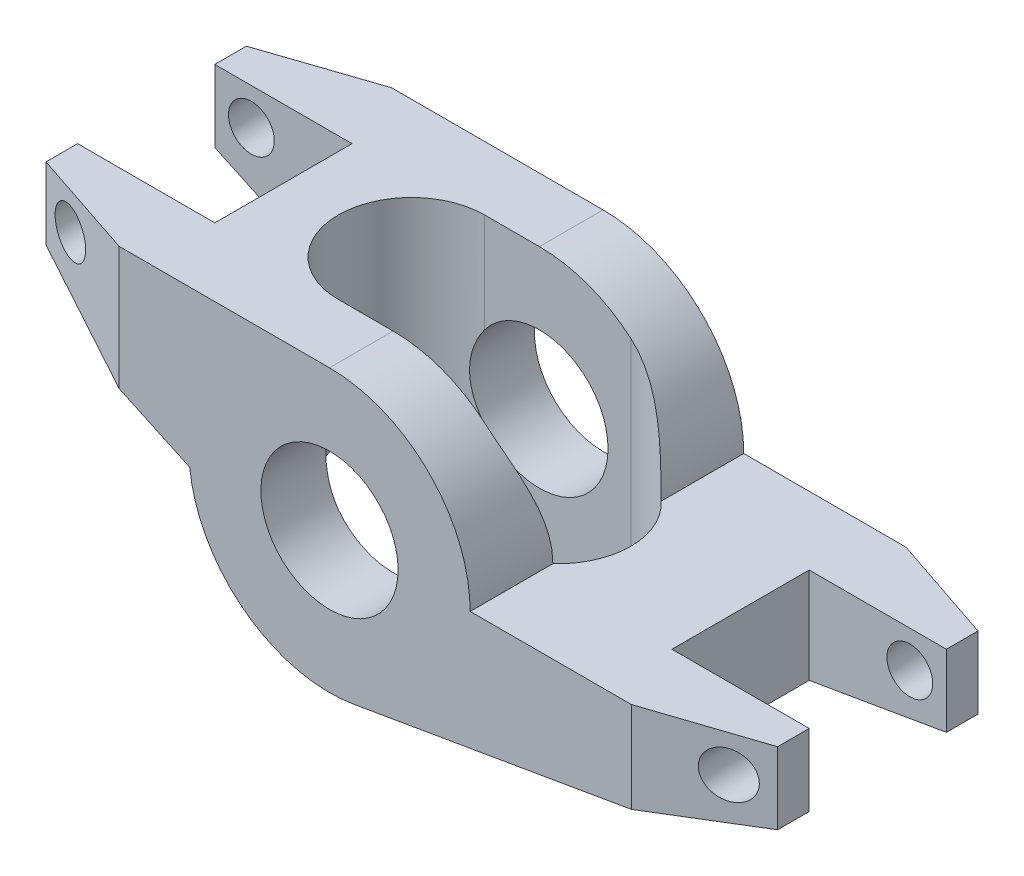
SolidWorks part; units mm, degrees
ref_plane "Front Plane" through (0, 0, 0) normal (0, 0, 1) x (1, 0, 0)
ref_plane "Top Plane" through (0, 0, 0) normal (0, 1, 0) x (1, 0, 0)
ref_plane "Right Plane" through (0, 0, 0) normal (1, 0, 0) x (0, 0, -1)
sketch "Sketch1" plane through (0, 0, 0) normal (0, 0, 1) x (1, 0, 0)
  line L0 (0, 9.77) -> (-22.23, 9.77)
  line L1 (-22.23, 9.77) -> (-22.23, 4.77)
  line L2 (-22.23, 4.77) -> (-9.7115, -1.0675)
  line L3 (9.77, 0) -> (28.58, 0)
  line L4 (28.58, 0) -> (28.58, -5)
  line L5 (28.58, -5) -> (1.6553, -9.6287)
  arc A0 (9.77, 0) -> (0, 9.77) centre (0, 0) ccw
  circle A1 centre (0, 0) radius 4.765
  arc A2 (-9.7115, -1.0675) -> (1.6553, -9.6287) centre (0, 0) ccw
  dimension "D1" = 19.54
  dimension "D2" = 9.53
  dimension "D3" = 22.23
  dimension "D4" = 5
  dimension "D5" = 25
  dimension "D6" = 28.58
extrude "Boss-Extrude1" add sketch "Sketch1" along normal mid plane 19
chamfer "Chamfer4" distance 7.54 distance2 2.54 2 edges at (28.58, -2.5, -9.5) (-22.23, 7.27, -9.5)
chamfer "Chamfer5" distance 2.54 distance2 7.62 2 edges at (-22.23, 7.27, 9.5) (28.58, -2.5, 9.5)
sketch "Sketch2" plane through (0, 0, 0) normal (0, 1, 0) x (1, 0, 0)
  line L0 (-22.23, -6.96) -> (-22.23, 6.96) construction
  line L1 (-22.23, 4.765) -> (-12.7, 4.765)
  line L2 (-22.23, 4.765) -> (-22.23, -4.765)
  line L3 (-22.23, -4.765) -> (-12.7, -4.765)
  line L4 (-12.7, 4.765) -> (-12.7, -4.765)
  line L5 (28.58, -6.96) -> (28.58, 6.96) construction
  line L6 (28.58, 4.765) -> (19.05, 4.765)
  line L7 (28.58, 4.765) -> (28.58, -4.765)
  line L8 (28.58, -4.765) -> (19.05, -4.765)
  line L9 (19.05, 4.765) -> (19.05, -4.765)
  point P12 (-22.23, 0)
  point P14 (19.05, 0)
  dimension "D1" = 9.53
  dimension "D2" = 9.53
  dimension "D3" = 9.53
  dimension "D4" = 9.53
extrude "Cut-Extrude1" cut sketch "Sketch2" along normal through all both and the other way through all contours L2 L1 L4 L3 | L7 L6 L9 L8
sketch "Sketch3" plane through (0, 0, 0) normal (0, 1, 0) x (1, 0, 0)
  line L0 (-3.81, 0) -> (6.35, 0) construction
  line L1 (-3.81, 5.08) -> (6.35, 5.08)
  line L2 (-3.81, -5.08) -> (6.35, -5.08)
  line L3 (-12.7, 4.765) -> (-12.7, -4.765) construction
  arc A0 (-3.81, 5.08) -> (-3.81, -5.08) centre (-3.81, 0) ccw
  arc A1 (6.35, -5.08) -> (6.35, 5.08) centre (6.35, 0) ccw
  point P3 (1.27, 0)
  point P8 (0, 0)
  dimension "D2" = 5.08
  dimension "D1" = 8.89
  dimension "D3" = 10.16
extrude "Cut-Extrude2" cut sketch "Sketch3" against normal through all both and the other way through all
sketch "Sketch4" plane through (0, 0, 0) normal (0, 0, 1) x (1, 0, 0)
  line L0 (-22.23, 4.77) -> (-22.23, 9.77) construction
  line L1 (-22.23, 9.77) -> (-14.61, 9.77) construction
  line L2 (20.96, 0) -> (28.58, 0) construction
  line L3 (28.58, 0) -> (28.58, -5) construction
  circle A0 centre (-19.69, 7.23) radius 1.59
  circle A1 centre (26.04, -2.54) radius 1.59
  point P8 (-24.3368, 4.9575)
  point P13 (25.6618, 0)
  point P14 (0, 0)
  dimension "D1" = 3.18
  dimension "D2" = 2.54
  dimension "D3" = 2.54
  dimension "D4" = 2.54
  dimension "D5" = 2.54
extrude "Cut-Extrude3" cut sketch "Sketch4" along normal through all both and the other way through all
